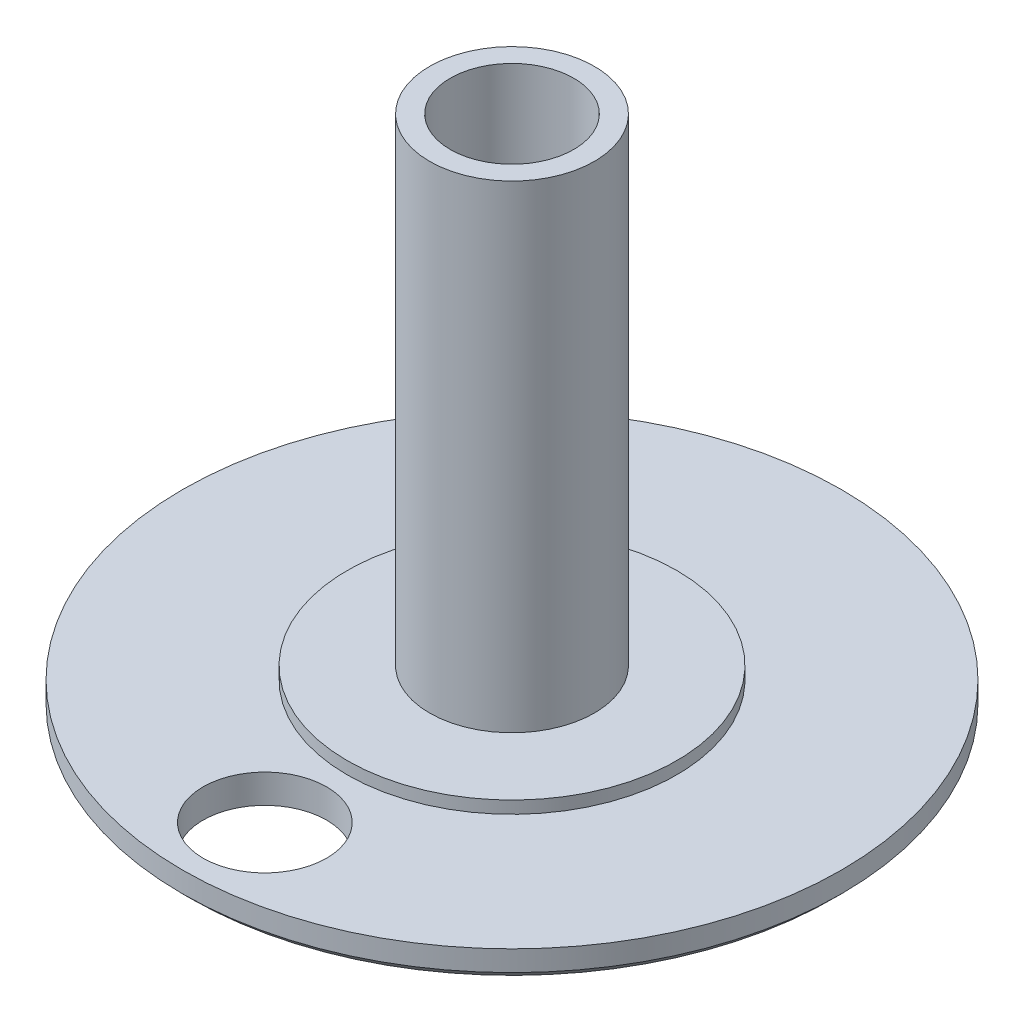
SolidWorks part; units mm, degrees
ref_plane "Front Plane" through (0, 0, 0) normal (0, 0, 1) x (1, 0, 0)
ref_plane "Top Plane" through (0, 0, 0) normal (0, 1, 0) x (1, 0, 0)
ref_plane "Right Plane" through (0, 0, 0) normal (1, 0, 0) x (0, 0, -1)
sketch "Sketch1" plane through (0, 0, 0) normal (0, 1, 0) x (1, 0, 0)
  circle A0 centre (0, 0) radius 8
  dimension "D1" = 16
extrude "Boss-Extrude1" add sketch "Sketch1" along normal blind 0.7
sketch "Sketch2" plane through (0, 0.7, 0) normal (0, 1, 0) x (1, 0, 0)
  circle A0 centre (0, 0) radius 4
  dimension "D1" = 8
extrude "Boss-Extrude2" add sketch "Sketch2" along normal blind 0.3
sketch "Sketch3" plane through (0, 1, 0) normal (0, 1, 0) x (1, 0, 0)
  circle A0 centre (0, 0) radius 2
  dimension "D1" = 4
extrude "Boss-Extrude3" add sketch "Sketch3" along normal blind 11.6
sketch "Sketch4" plane through (0, 12.6, 0) normal (0, 1, 0) x (1, 0, 0)
  circle A0 centre (0, 0) radius 1.5
  dimension "D1" = 3
extrude "Cut-Extrude1" cut sketch "Sketch4" against normal blind 8.5 contours A0
sketch "Sketch5" plane through (0, 0, 0) normal (0, -1, 0) x (1, 0, 0)
  circle A0 centre (0, 6) radius 1.5
  dimension "D1" = 3
  dimension "D2" = 6
extrude "Cut-Extrude2" cut sketch "Sketch5" against normal through all
chamfer "Chamfer1" distance 0.2 angle 45 1 edges at (0, 0, 8)
